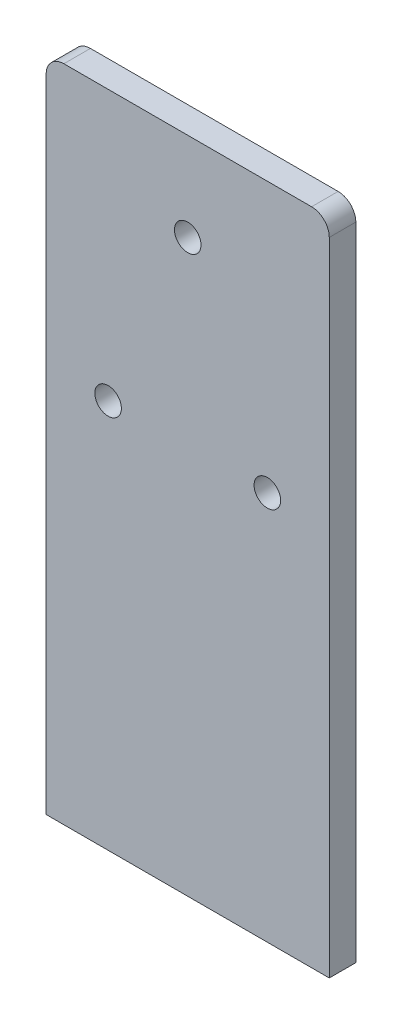
SolidWorks part; units mm, degrees
material "MDF"
ref_plane "Alzado" through (0, 0, 0) normal (0, 0, 1) x (1, 0, 0)
ref_plane "Planta" through (0, 0, 0) normal (0, 1, 0) x (1, 0, 0)
ref_plane "Vista lateral" through (0, 0, 0) normal (1, 0, 0) x (0, 0, -1)
sketch "Croquis1" plane through (0, 0, 0) normal (0, 0, 1) x (1, 0, 0)
  line L1 (-16, 37.25) -> (16, 37.25)
  line L2 (-16, 37.25) -> (-16, -37.25)
  line L3 (-16, -37.25) -> (16, -37.25)
  line L4 (16, 37.25) -> (16, -37.25)
  line L5 (-16, 37.25) -> (16, -37.25) construction
  line L6 (-16, -37.25) -> (16, 37.25) construction
  circle A0 centre (0, 27.25) radius 1.5
  circle A1 centre (-9, 6.75) radius 1.5
  circle A2 centre (9, 6.75) radius 1.5
  point P0 (0, 0)
  dimension "D3" = 3
  dimension "D1" = 32
  dimension "D2" = 74.5
  dimension "D4" = 16
  dimension "D5" = 20.5
  dimension "D6" = 25
  dimension "D7" = 7
  dimension "D8" = 44
extrude "Saliente-Extruir1" add sketch "Croquis1" along normal mid plane 3
fillet "Redondeo1" radius 2 2 edges at (16, 37.25, 0) (-16, 37.25, 0)
